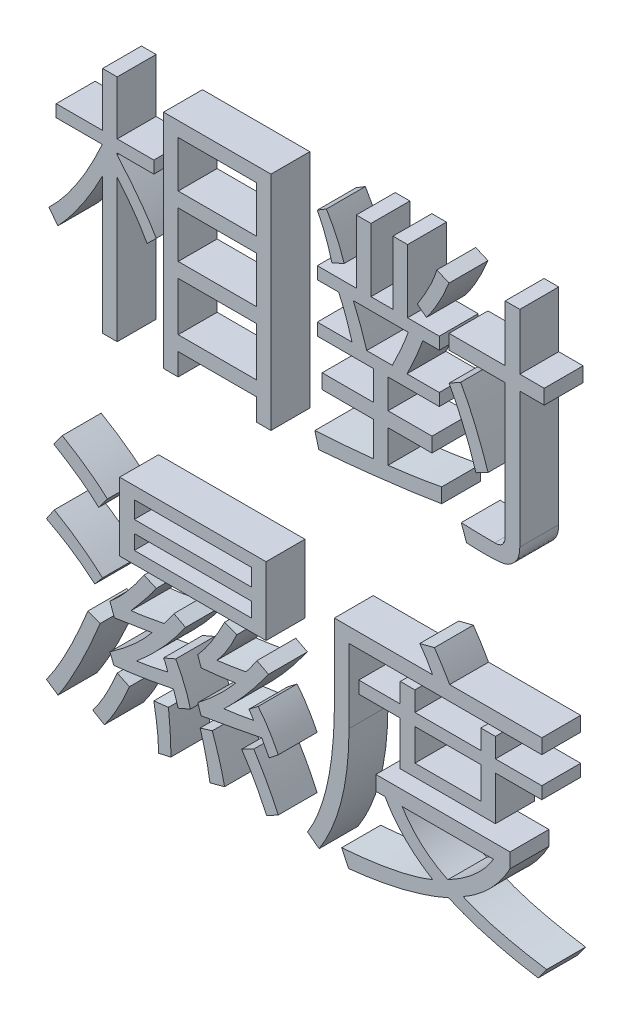
SolidWorks part; units mm, degrees
ref_plane "前基準面" through (0, 0, 0) normal (0, 0, 1) x (1, 0, 0)
ref_plane "上基準面" through (0, 0, 0) normal (0, 1, 0) x (1, 0, 0)
ref_plane "右基準面" through (0, 0, 0) normal (1, 0, 0) x (0, 0, -1)
sketch "草圖2" plane through (0, 0, 0) normal (0, 0, 1) x (1, 0, 0)
  text T0 "相對\r\n濕度" font "微軟正黑體" height 18
extrude "填料-伸長1" add sketch "草圖2" along normal blind 3.5
